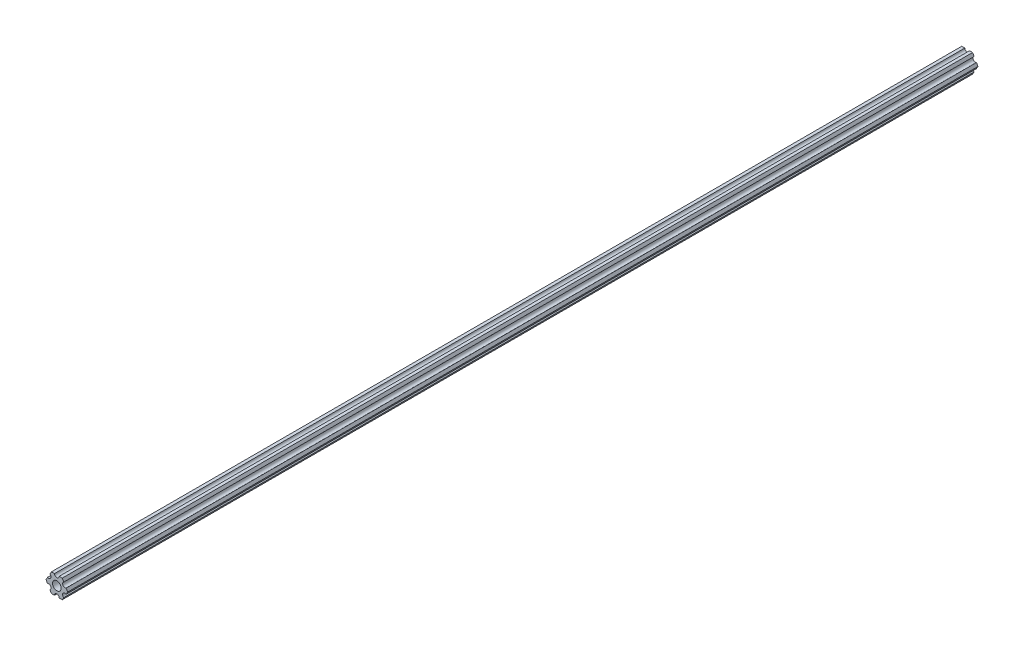
SolidWorks part; units mm, degrees
material "6061 Alloy"
ref_plane "Front Plane" through (0, 0, 0) normal (0, 0, 1) x (1, 0, 0)
ref_plane "Top Plane" through (0, 0, 0) normal (0, 1, 0) x (1, 0, 0)
ref_plane "Right Plane" through (0, 0, 0) normal (1, 0, 0) x (0, 0, -1)
sketch "Sketch1" plane through (0, 0, 0) normal (0, 0, 1) x (1, 0, 0)
  line L0 (3.6662, -6.35) -> (4.7055, -4.5498)
  line L1 (6.293, -1.8002) -> (7.3323, 0)
  line L2 (7.3323, 0) -> (6.293, 1.8002)
  line L3 (4.7055, 4.5498) -> (3.6662, 6.35)
  line L4 (3.6662, 6.35) -> (1.5875, 6.35)
  line L5 (-1.5875, 6.35) -> (-3.6662, 6.35)
  line L6 (-3.6662, 6.35) -> (-4.7055, 4.5498)
  line L7 (-6.293, 1.8002) -> (-7.3323, 0)
  line L8 (-7.3323, 0) -> (-6.293, -1.8002)
  line L9 (-4.7055, -4.5498) -> (-3.6662, -6.35)
  line L10 (-3.6662, -6.35) -> (-1.5875, -6.35)
  line L11 (1.5875, -6.35) -> (3.6662, -6.35)
  circle A0 centre (0, 0) radius 2.9337
  arc A1 (4.7055, -4.5498) -> (6.293, -1.8002) centre (5.4993, -3.175) cw
  arc A2 (6.293, 1.8002) -> (4.7055, 4.5498) centre (5.4993, 3.175) cw
  arc A3 (1.5875, 6.35) -> (-1.5875, 6.35) centre (0, 6.35) cw
  arc A4 (-4.7055, 4.5498) -> (-6.293, 1.8002) centre (-5.4993, 3.175) cw
  arc A5 (-6.293, -1.8002) -> (-4.7055, -4.5498) centre (-5.4993, -3.175) cw
  arc A6 (-1.5875, -6.35) -> (1.5875, -6.35) centre (0, -6.35) cw
  dimension "D1" = 5.8674
  dimension "D2" = 1.5875
  dimension "D3" = 3.6662
  dimension "D4" = 5.4993
extrude "Boss-Extrude1" add sketch "Sketch1" against normal blind 615.95
